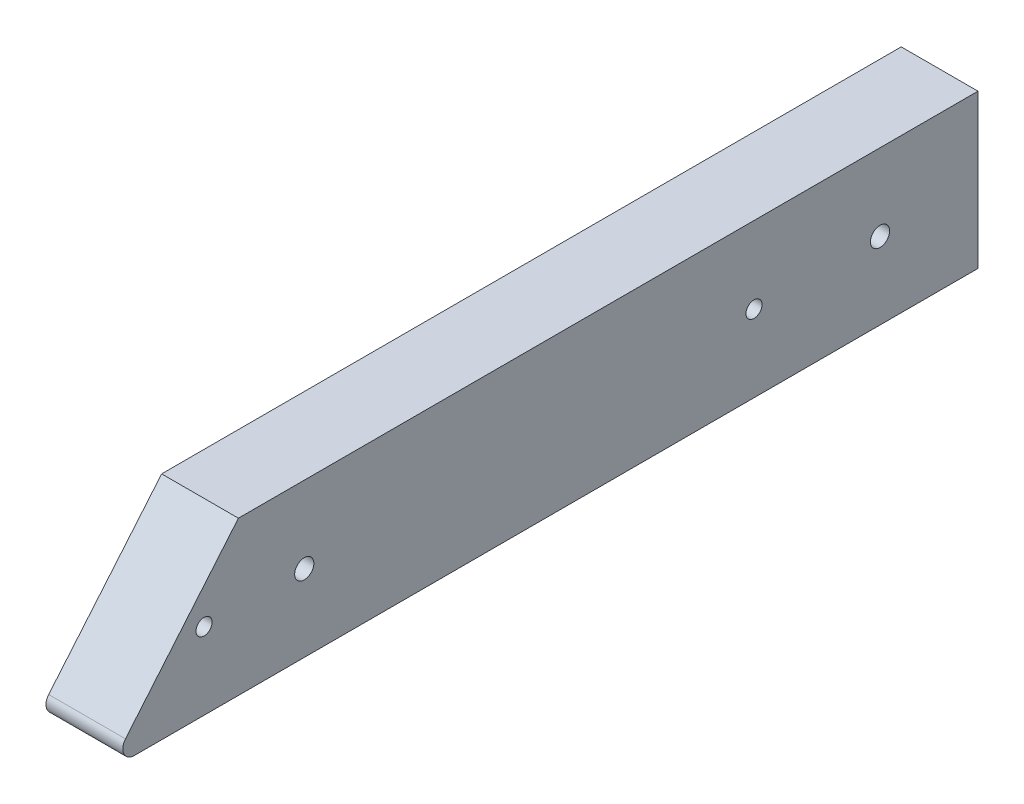
SolidWorks part; units mm, degrees
ref_plane "Płaszczyzna przednia" through (0, 0, 0) normal (0, 0, 1) x (1, 0, 0)
ref_plane "Płaszczyzna górna" through (0, 0, 0) normal (0, 1, 0) x (1, 0, 0)
ref_plane "Płaszczyzna prawa" through (0, 0, 0) normal (1, 0, 0) x (0, 0, -1)
sketch "setup sketch" plane through (0, 0, 0) normal (1, 0, 0) x (0, 0, -1)
  line L0 (68.5389, 81.6815) -> (0, 0) construction
  line L1 (0, 0) -> (-35, 0) construction
  line L2 (0, 28.015) -> (0, -22.9624) construction
  line L3 (-35, 0) -> (-20.5388, 17.2341) construction
  line L4 (-20.5388, 17.2341) -> (0, 0) construction
  dimension "D1" = 50
  dimension "D2" = 70
ref_plane "Plane1" through (0, 0, 0) normal (0, -0.766, 0.6428) x (0, -0.6428, -0.766)
sketch "Sketch3" plane through (0, 0, 0) normal (1, 0, 0) x (0, 0, -1)
  line L0 (-62.6943, 20) -> (-96.2583, -20)
  line L1 (-96.2583, -20) -> (130, -20)
  line L2 (130, -20) -> (130, 20)
  line L3 (130, 20) -> (-62.6943, 20)
  line L4 (64.18, 76.4868) -> (0, 0) construction
  line L5 (0, 0) -> (-35, 0) construction
  line L6 (39.6758, 142) -> (-229.6751, -179) construction
  dimension "D1" = 40
  dimension "D2" = 130
extrude "Boss-Extrude1" add sketch "Sketch3" along normal blind 20
sketch "Sketch2" plane through (0, 0, 0) normal (0, -0.766, 0.6428) x (0, -0.6428, -0.766)
  line L0 (-26.8116, 0) -> (-26.8116, 3.5052) construction
  line L1 (-25.3116, 4) -> (-28.3116, 4)
  line L2 (-25.3116, 4) -> (-25.3116, 11)
  line L3 (-25.3116, 11) -> (-28.3116, 11)
  line L4 (-28.3116, 4) -> (-28.3116, 11)
  line L5 (-26.8116, 0) -> (-40.8116, 0) construction
  dimension "D1" = 4
  dimension "D2" = 3
  dimension "D3" = 7
  dimension "D4" = 14
hole_wizard "M6 Tapped Hole1" positions "Sketch5" profile "Sketch4" tap size "M6" standard "DIN" end condition through all
sketch "Sketch5" plane through (0, 0, 0) normal (-1, 0, 0) x (0, 0, 1)
  line L0 (0, 0) -> (35, 0) construction
  line L1 (62.6943, 20) -> (96.2583, -20) construction
  point P0 (45.5357, 0)
  point P7 (-104.4643, 0)
  dimension "D1" = 26
sketch "Sketch4" plane through (0, 0, 45.5357) normal (0, 1, 0) x (0, 0, 1)
  line L0 (0, 0) -> (0, 20)
  line L1 (0, 20) -> (2.5, 20)
  line L2 (2.5, 20) -> (2.5, 0)
  line L5 (2.5, 0) -> (0, 0)
  line L11 (0, -6.35) -> (0, 107.95) construction
  dimension "Thru Tap Drill Dia." = 5
  dimension "Thru Tap Drill Depth" = 20
cosmetic thread "Hole Thread1" parameters "D2"=6
cosmetic thread "Gwint otworu1" parameters "D2"=6
fillet "Fillet1" radius 3 1 edges at (10, -20, 96.2583)
hole_wizard "Otwór gwintowany M51" positions "Szkic2" profile "Szkic1" tap size "M5" standard "DIN" end condition through all
sketch "Szkic2" plane through (20, 0, 0) normal (1, 0, 0) x (0, 0, -1)
  point P0 (-71.6439, 0)
  point P3 (71.6439, 0)
sketch "Szkic1" plane through (20, 0, 71.6439) normal (0, 1, 0) x (0, 0, -1)
  line L0 (0, 0) -> (0, 20)
  line L1 (0, 20) -> (2.1, 20)
  line L2 (2.1, 20) -> (2.1, 0)
  line L5 (2.1, 0) -> (0, 0)
  line L11 (0, -6.35) -> (0, 107.95) construction
  dimension "Średnica otworu gwintowanego na wylot" = 4.2
  dimension "Głębokość otworu gwintowanego na wylot" = 20
cosmetic thread "Gwint otworu2" parameters "D2"=5
cosmetic thread "Gwint otworu3" parameters "D2"=5
